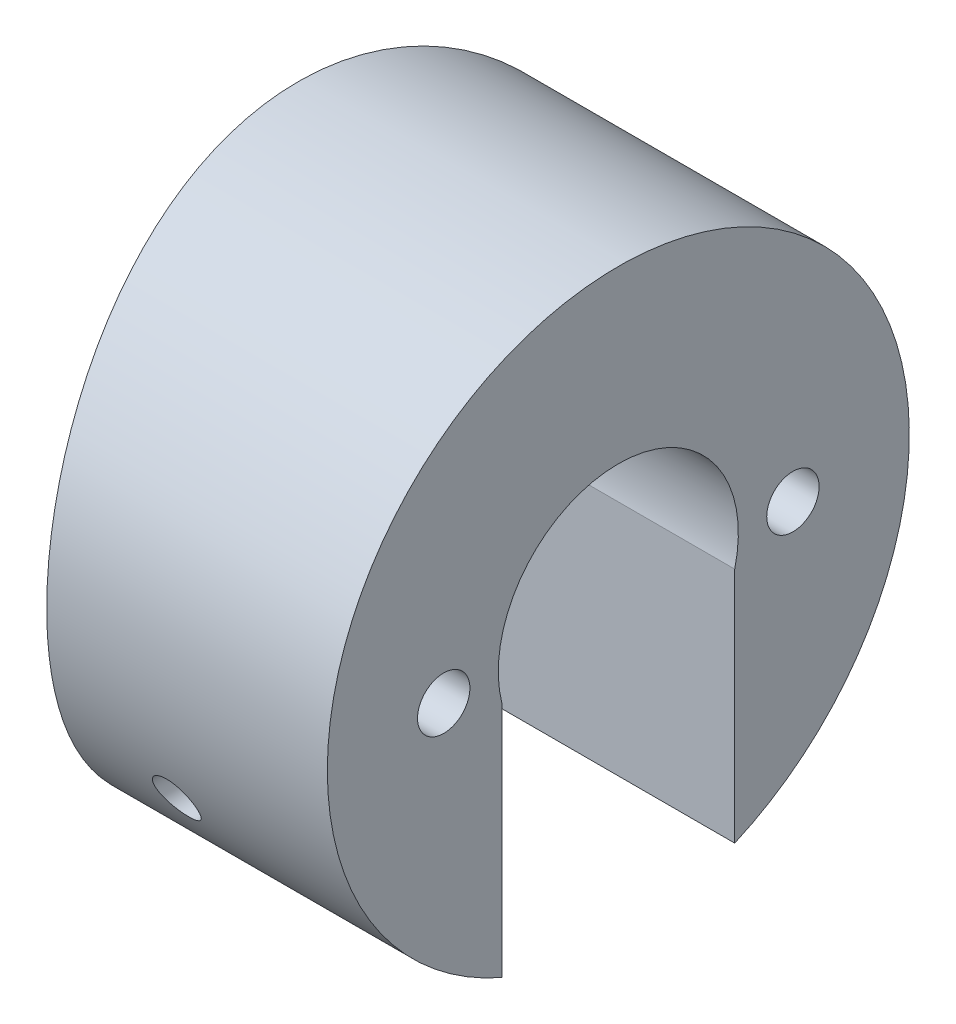
SolidWorks part; units mm, degrees
ref_plane "Plano frontal" through (0, 0, 0) normal (0, 0, 1) x (1, 0, 0)
ref_plane "Plano superior" through (0, 0, 0) normal (0, 1, 0) x (1, 0, 0)
ref_plane "Plano direito" through (0, 0, 0) normal (1, 0, 0) x (0, 0, -1)
sketch "Sketch1" plane through (0, 0, 0) normal (1, 0, 0) x (0, 0, -1)
  circle A0 centre (0, 0) radius 20
  dimension "D1" = 40
extrude "Bloco" add sketch "Sketch1" along normal blind 22
sketch "Sketch2" plane through (22, 0, 0) normal (1, 0, 0) x (0, 0, -1)
  line L0 (-8, -18.3303) -> (-8, -2.0156)
  line L1 (8, -2.0156) -> (8, -18.3303)
  arc A0 (8, -2.0156) -> (-8, -2.0156) centre (0, 0) ccw
  circle A1 centre (0, 0) radius 20 construction
  arc A2 (-8, -18.3303) -> (8, -18.3303) centre (0, 0) ccw
  dimension "D1" = 16.5
  dimension "D2" = 8
  dimension "D3" = 16
extrude "Encaixe do Potenciômetro" cut sketch "Sketch2" against normal blind 19
hole_wizard "Furo de Fixação - Parafuso M3" positions "Sketch5" profile "Sketch6" countersink size "M3" standard "ANSI Metric" end condition up to next
sketch "Sketch5" plane through (0, 0, 0) normal (-1, 0, 0) x (0, 0, 1)
  point P10 (-12, 0)
  point P12 (12, 0)
  dimension "D1" = 24
  dimension "D2" = 12
sketch "Sketch6" plane through (0, 0, -12) normal (0, 1, 0) x (0, 0, 1)
  line L0 (0, 0) -> (0, 22)
  line L1 (0, 22) -> (1.8, 22)
  line L2 (1.8, 22) -> (1.8, 1.56)
  line L3 (1.8, 1.56) -> (3.36, 0)
  line L5 (3.36, 0) -> (0, 0)
  line L6 (-1.8, 1.56) -> (-3.36, 0) construction
  line L11 (0, -6.35) -> (0, 107.95) construction
  dimension "Thru Hole Dia." = 3.6
  dimension "Thru Hole Depth" = 22
  dimension "Near C'Sink Dia." = 6.72
  dimension "Near C'Sink Angle" = 90
sketch "Sketch7" plane through (0, 0, 0) normal (0, 1, 0) x (1, 0, 0)
  circle A0 centre (75, 0) radius 75
  circle A1 centre (75, 0) radius 100
  dimension "D2" = 200
  dimension "D1" = 75
extrude "Corte - Arredondamento" cut sketch "Sketch7" against normal through all and the other way through all
sketch "Sketch8" plane through (0, 0, 0) normal (0, 0, 1) x (1, 0, 0)
  line L0 (22, -18.3303) -> (22, 20) construction
  circle A0 centre (9.5, -9) radius 1.5
  dimension "D1" = 3
  dimension "D2" = 12.5
  dimension "D3" = 9
extrude "Furo de Fixação - Potenciômetro" cut sketch "Sketch8" along normal up to next
